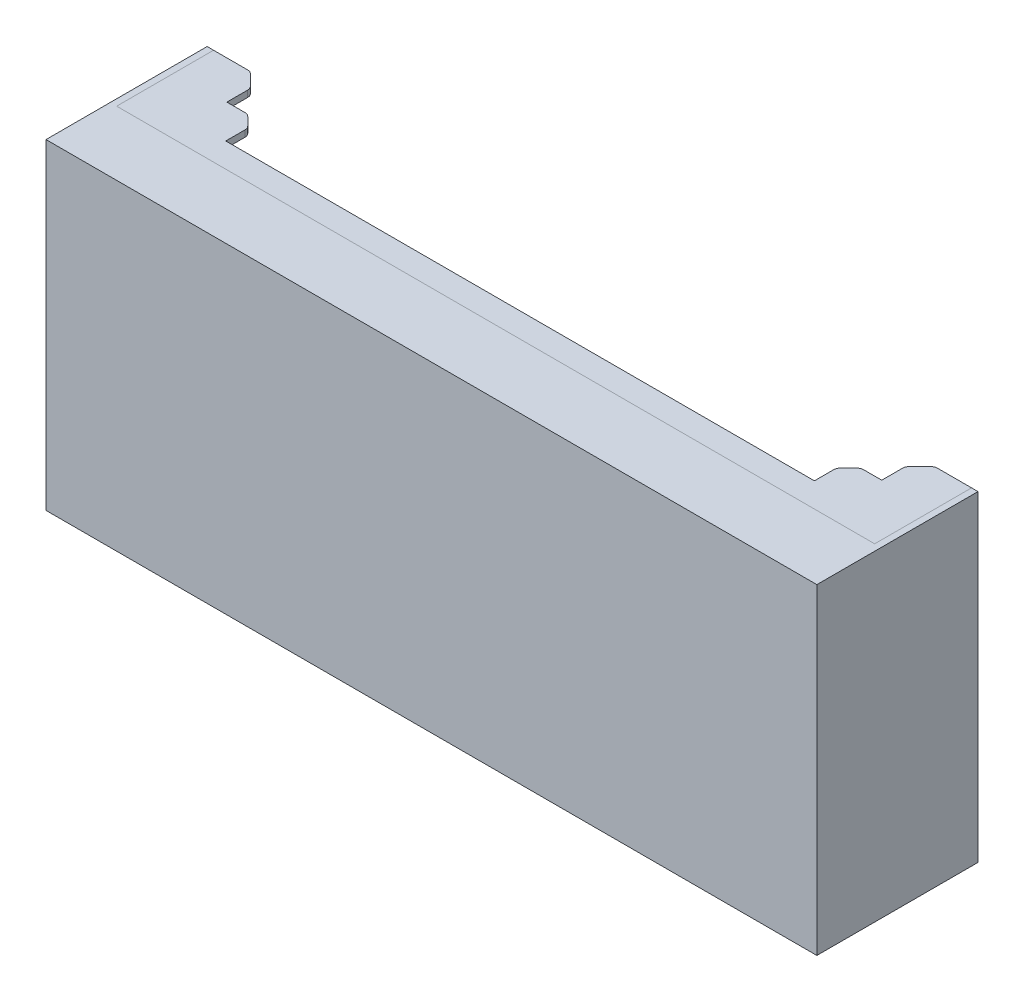
SolidWorks part; units mm, degrees
ref_plane "Front Plane" through (0, 0, 0) normal (0, 0, 1) x (1, 0, 0)
ref_plane "Top Plane" through (0, 0, 0) normal (0, 1, 0) x (1, 0, 0)
ref_plane "Right Plane" through (0, 0, 0) normal (1, 0, 0) x (0, 0, -1)
sketch "Sketch2" plane through (0, 0, 0) normal (0, 0, 1) x (1, 0, 0)
  line L1 (0, 0) -> (-120, 0)
  line L2 (0, 0) -> (0, 50)
  line L3 (0, 50) -> (-120, 50)
  line L4 (-120, 0) -> (-120, 50)
  dimension "D1" = 120
  dimension "D2" = 50
extrude "Boss-Extrude1" add sketch "Sketch2" along normal blind 10
sketch "Sketch5" plane through (0, 0, 0) normal (0, 0, -1) x (-1, 0, 0)
  line L0 (0, 0) -> (0, 50) construction
  line L1 (0, 23.4268) -> (120, 23.4268)
  line L2 (0, 23.4268) -> (0, 22.4268)
  line L3 (0, 22.4268) -> (120, 22.4268)
  line L4 (120, 23.4268) -> (120, 22.4268)
  line L5 (120, 50) -> (120, 0) construction
  line L6 (120, 22.9268) -> (0, 22.9268) construction
  dimension "D1" = 1
extrude "Boss-Extrude2" add sketch "Sketch5" along normal blind 15
sketch "Sketch6" plane through (0, 0, 0) normal (1, 0, 0) x (0, 0, -1)
  line L1 (0, 50) -> (15.0863, 50)
  line L2 (0, 50) -> (0, 0)
  line L3 (0, 0) -> (15.0863, 0)
  line L4 (15.0863, 50) -> (15.0863, 0)
extrude "Boss-Extrude5" add sketch "Sketch6" against normal blind 1
sketch "Sketch7" plane through (-120, 0, 0) normal (-1, 0, 0) x (0, 0, 1)
  line L0 (-15.0863, 0) -> (-15.0863, 50) construction
  line L1 (0, 50) -> (-15.0863, 50)
  line L2 (0, 50) -> (0, 0)
  line L3 (0, 0) -> (-15.0863, 0)
  line L4 (-15.0863, 50) -> (-15.0863, 0)
  line L5 (-15.0863, 50) -> (0, 50) construction
extrude "Boss-Extrude6" add sketch "Sketch7" against normal blind 1
sketch "Sketch9" plane through (0, 0, 0) normal (0, -1, 0) x (1, 0, 0)
  line L0 (-60, 10) -> (-60, -28.6988) construction
  line L1 (-120, 10) -> (0, 10) construction
  line L2 (-1, -15.0863) -> (-6.7321, -15.0863)
  line L3 (-6.7321, -15.0863) -> (-9.0266, -12.7917)
  line L4 (-9.0266, -12.7917) -> (-9.0266, -9.1281)
  line L5 (-9.0266, -9.1281) -> (-12.2795, -9.1281)
  line L6 (-12.2795, -9.1281) -> (-14.1831, -7.2246)
  line L7 (-105.8169, -7.2246) -> (-105.8169, -3.8013)
  line L8 (-119, 0) -> (-1, 0) construction
  line L9 (-105.8169, -3.8013) -> (-14.1831, -3.8013)
  line L10 (-1, -15.0863) -> (-1, 0)
  line L11 (-1, 0) -> (-14.1831, 0)
  line L12 (-119, -15.0863) -> (-119, 0)
  line L13 (-119, 0) -> (-105.8169, 0)
  line L14 (-60, -3.8013) -> (-60, 0)
  line L15 (-107.7205, -9.1281) -> (-105.8169, -7.2246)
  line L16 (-110.9734, -9.1281) -> (-107.7205, -9.1281)
  line L17 (-110.9734, -12.7917) -> (-110.9734, -9.1281)
  line L18 (-113.2679, -15.0863) -> (-110.9734, -12.7917)
  line L19 (-119, -15.0863) -> (-113.2679, -15.0863)
  line L20 (-60, 0) -> (-105.8169, 0)
  line L21 (-14.1831, -7.2246) -> (-14.1831, -3.8013)
  point P20 (-60, 0)
  line M13 (-119, -15.0863) -> (-119, 0)
  line M14 (-119, 0) -> (-1, 0)
  line M15 (-1, 0) -> (-1, -15.0863)
extrude "Boss-Extrude7" add sketch "Sketch9" along normal blind 1 separate body contours L21 L6 L5 L4 L3 L2 L14 L9 M15 M14 | L19 L18 L17 L16 L15 L7 L9 L14 M13 M14
pattern_linear "LPattern2" count 2 spacing 50 along (0, 1, 0) of "Boss-Extrude7"
fillet "Fillet1" radius 1 8 edges at (-14.1831, 49.5, -7.2246) (-12.2795, 49.5, -9.1281) (-9.0266, 49.5, -12.7917) (-6.7321, 49.5, -15.0863) (-105.8169, 49.5, -7.2246) (-107.7205, 49.5, -9.1281) (-113.2679, 49.5, -15.0863) (-110.9734, 49.5, -12.7917)
fillet "Fillet2" radius 1 8 edges at (-105.8169, -0.5, -7.2246) (-107.7205, -0.5, -9.1281) (-110.9734, -0.5, -12.7917) (-113.2679, -0.5, -15.0863) (-14.1831, -0.5, -7.2246) (-12.2795, -0.5, -9.1281) (-9.0266, -0.5, -12.7917) (-6.7321, -0.5, -15.0863)
sketch "Sketch10" plane through (-1, 0, 0) normal (-1, 0, 0) x (0, 0, 1)
  line L0 (0, 36.7134) -> (-15.0863, 36.7134) construction
  line L1 (0, 50) -> (0, 23.4268) construction
  line L2 (-15.0863, 0) -> (-15.0863, 50) construction
  circle A0 centre (-7.5431, 36.7134) radius 4
  dimension "D1" = 8
extrude "Boss-Extrude8" add sketch "Sketch10" along normal blind 1 contours A0
sketch "Sketch11" plane through (-1, 0, 0) normal (-1, 0, 0) x (0, 0, 1)
  line L0 (-7.5, 22.4268) -> (-7.5431, 0) construction
  line L1 (0, 22.4268) -> (-15, 22.4268) construction
  line L2 (0, 0) -> (-15.0863, 0) construction
  circle A0 centre (-7.5216, 11.2134) radius 4
  dimension "D1" = 8
extrude "Boss-Extrude10" add sketch "Sketch11" along normal blind 1
sketch "Sketch12" plane through (-2, 0, 0) normal (-1, 0, 0) x (0, 0, 1)
  circle A0 centre (-7.5431, 36.7134) radius 1
  circle A1 centre (-7.5216, 11.2134) radius 1
  dimension "D1" = 2
  dimension "D2" = 2
extrude "Boss-Extrude11" add sketch "Sketch12" along normal blind 0.5
sketch "Sketch13" plane through (-119, 0, 0) normal (1, 0, 0) x (0, 0, -1)
  line L0 (7.5431, 49) -> (7.5, 23.4268) construction
  line L1 (15.0863, 49) -> (0, 49) construction
  line L2 (15, 23.4268) -> (0, 23.4268) construction
  line L4 (7.5271, 39.487) -> (10.7059, 39.487)
  line L5 (7.5271, 39.487) -> (7.5271, 36.2633)
  line L6 (7.5271, 36.2633) -> (10.7059, 36.2633)
  line L7 (10.7059, 39.487) -> (10.7059, 36.2633)
  line L9 (7.5, 22.4268) -> (7.5, 0) construction
  line L10 (0, 22.4268) -> (15, 22.4268) construction
  line L11 (7.5, 15.2144) -> (10.6788, 15.2144)
  line L12 (7.5, 15.2144) -> (7.5, 11.9907)
  line L13 (7.5, 11.9907) -> (10.6788, 11.9907)
  line L14 (10.6788, 15.2144) -> (10.6788, 11.9907)
extrude "Boss-Extrude12" add sketch "Sketch13" along normal blind 0.5
sketch "Sketch14" plane through (0, 39.487, 0) normal (0, 1, 0) x (1, 0, 0)
  line L0 (-118.5, 10.7059) -> (-118.0358, 10.4096)
  line L1 (-118.0358, 10.4096) -> (-118.0358, 9.4416)
  line L2 (-118.0358, 9.4416) -> (-118.0358, 8.3466)
  line L3 (-118.0358, 8.3466) -> (-118.5, 8.3466)
  line L4 (-118.5, 10.7059) -> (-118.5, 7.5271) construction
  line L5 (-118.5, 8.3466) -> (-118.5, 10.7059)
extrude "Boss-Extrude13" add sketch "Sketch14" against normal blind 3.2
sketch "Sketch15" plane through (0, 11.9907, 0) normal (0, -1, 0) x (1, 0, 0)
  line L0 (-118.5, -10.6788) -> (-118.5, -8.3188)
  line L1 (-118.5, -8.3188) -> (-118.1422, -8.6188)
  line L2 (-118.1422, -8.6188) -> (-118.1422, -10.6788)
  line L3 (-118.1422, -10.6788) -> (-118.5, -10.6788)
  line L4 (-118.5, -7.5) -> (-118.5, -10.6788) construction
  line L6 (-118.5, -10.6788) -> (-119, -10.6788) construction
  dimension "D1" = 2.36
  dimension "D2" = 2.06
extrude "Boss-Extrude15" add sketch "Sketch15" against normal blind 3.2
